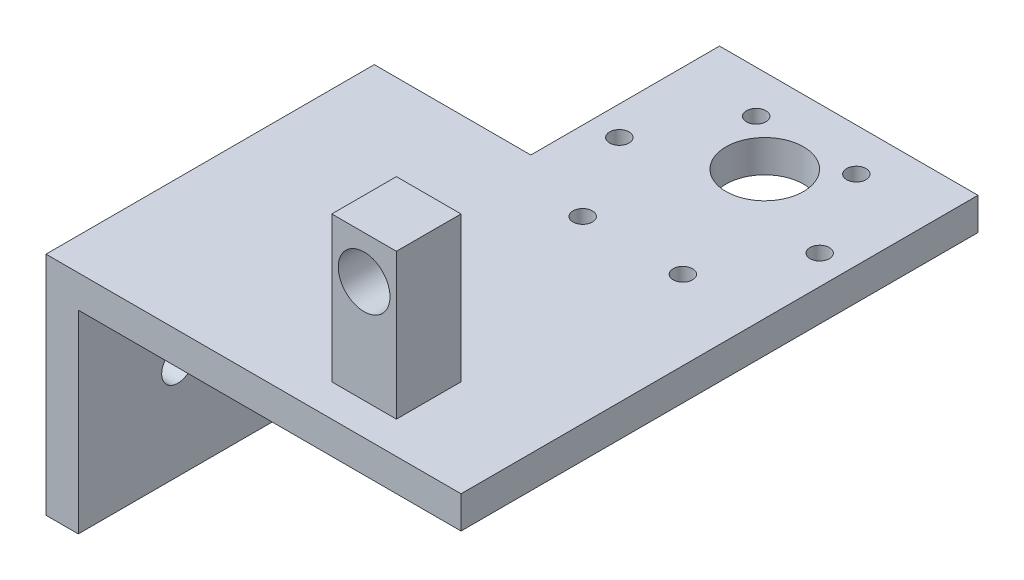
SolidWorks part; units mm, degrees
ref_plane "Front Plane" through (0, 0, 0) normal (0, 0, 1) x (1, 0, 0)
ref_plane "Top Plane" through (0, 0, 0) normal (0, 1, 0) x (1, 0, 0)
ref_plane "Right Plane" through (0, 0, 0) normal (1, 0, 0) x (0, 0, -1)
sketch "Sketch1" plane through (0, 0, 0) normal (0, 1, 0) x (1, 0, 0)
  circle A0 centre (-15.5, 0) radius 1.5
  circle A1 centre (-7.75, 13.4234) radius 1.5
  circle A2 centre (7.75, 13.4234) radius 1.5
  circle A3 centre (15.5, 0) radius 1.5
  circle A4 centre (7.75, -13.4234) radius 1.5
  circle A5 centre (-7.75, -13.4234) radius 1.5
  circle A6 centre (0, 7) radius 6
  point P17 (0, 0)
  dimension "D1" = 3
  dimension "D5" = 12
  dimension "D2" = 15.5
  dimension "D3" = 0
  dimension "D6" = 7
  dimension "D4" = 6
sketch "Sketch3" plane through (0, 0, 0) normal (0, 1, 0) x (1, 0, 0)
  line L1 (-20, 20) -> (20, 20)
  line L2 (-20, 20) -> (-20, -60)
  line L3 (-20, -60) -> (20, -60)
  line L4 (20, 20) -> (20, -60)
  dimension "D1" = 80
  dimension "D2" = 40
  dimension "D3" = 20
  dimension "D4" = 20
extrude "Boss-Extrude1" add sketch "Sketch3" along normal blind 5
extrude "Cut-Extrude3" cut sketch "Sketch1" along normal through all
sketch "Sketch4" plane through (0, 5, 0) normal (0, 1, 0) x (1, 0, 0)
  line L0 (-20, -60) -> (20, -60) construction
  line L1 (5, -45) -> (-5, -45)
  line L2 (5, -45) -> (5, -55)
  line L3 (5, -55) -> (-5, -55)
  line L4 (-5, -45) -> (-5, -55)
  dimension "D1" = 10
  dimension "D2" = 10
  dimension "D3" = 5
  dimension "D4" = 5
extrude "Boss-Extrude2" add sketch "Sketch4" along normal blind 22.5
sketch "Sketch5" plane through (0, 0, 55) normal (0, 0, 1) x (1, 0, 0)
  line L2 (-5, 5) -> (5, 5) construction
  circle A0 centre (0, 20.9) radius 4
  dimension "D1" = 8
  dimension "D2" = 15.9
extrude "Cut-Extrude4" cut sketch "Sketch5" against normal blind 8
sketch "Sketch6" plane through (-20, 0, 0) normal (-1, 0, 0) x (0, 0, 1)
  line L0 (-20, 5) -> (60, 5) construction
  line L1 (60, 0) -> (9.2, 0)
  line L2 (60, 0) -> (60, 5)
  line L3 (60, 5) -> (9.2, 5)
  line L4 (9.2, 0) -> (9.2, 5)
  dimension "D1" = 50.8
extrude "Boss-Extrude3" add sketch "Sketch6" along normal blind 24.225
sketch "Sketch8" plane through (0, 0, 0) normal (0, -1, 0) x (1, 0, 0)
  line L0 (-44.225, 60) -> (20, 60) construction
  line L1 (-44.225, 9.2) -> (-39.225, 9.2)
  line L2 (-44.225, 9.2) -> (-44.225, 60)
  line L3 (-44.225, 60) -> (-39.225, 60)
  line L4 (-39.225, 9.2) -> (-39.225, 60)
  dimension "D1" = 5
extrude "Boss-Extrude4" add sketch "Sketch8" along normal blind 30 contours L4 L3 L2 L1
sketch "Sketch9" plane through (-44.225, 0, 0) normal (-1, 0, 0) x (0, 0, 1)
  line L1 (9.2, -30) -> (60, -30) construction
  line L2 (60, -30) -> (60, 5) construction
  circle A0 centre (44.6, -15) radius 2.5
  circle A1 centre (24.6, -15) radius 2.5
  dimension "D1" = 5
  dimension "D2" = 5
  dimension "D3" = 20
  dimension "D4" = 15
  dimension "D5" = 15.4
extrude "Cut-Extrude5" cut sketch "Sketch9" against normal up to surface (5 mm away) up to face at (-39.225, -15, 34.6)
